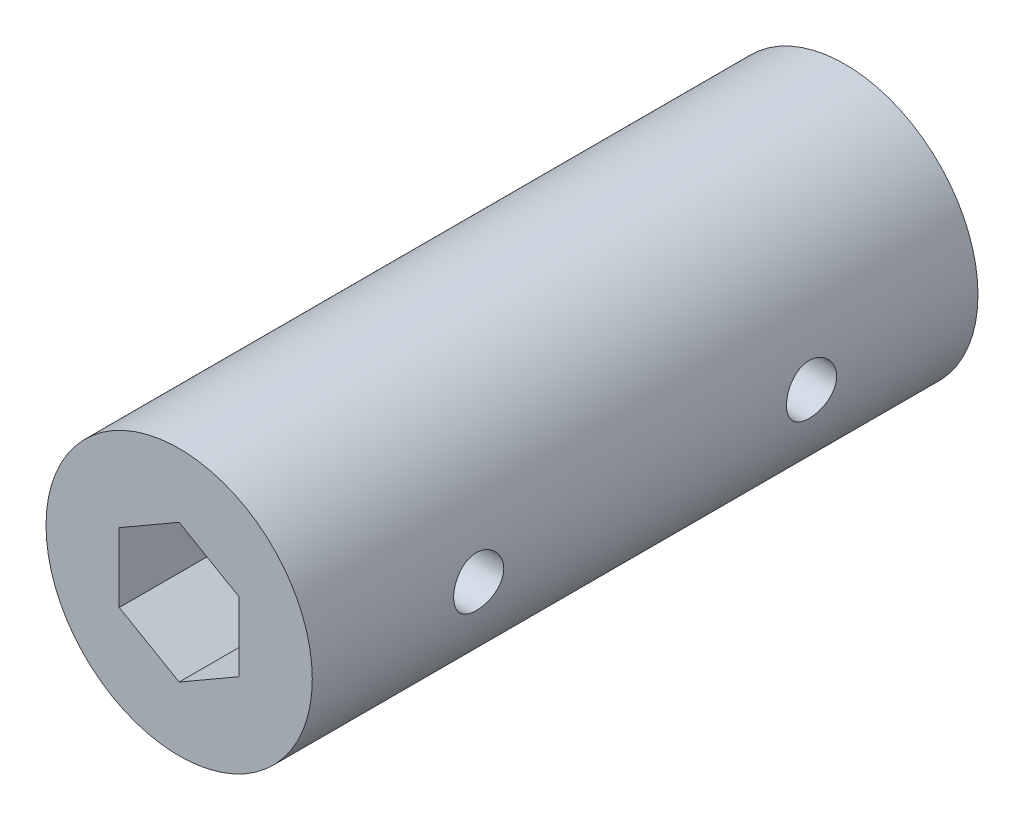
SolidWorks part; units mm, degrees
other "Adapter"
material "Nylon 101"
ref_plane "Front" through (0, 0, 0) normal (0, 0, 1) x (1, 0, 0)
ref_plane "Top" through (0, 0, 0) normal (0, 1, 0) x (1, 0, 0)
ref_plane "Right" through (0, 0, 0) normal (1, 0, 0) x (0, 0, -1)
sketch "MotorSke" plane through (0, 0, 0) normal (0, 0, 1) x (1, 0, 0)
  line L0 (1, 1.05) -> (1, -1.05)
  circle A0 centre (0, 0) radius 2
  arc A1 (1, 1.05) -> (1, -1.05) centre (0, 0) ccw
  dimension "D1" = 1.45
  dimension "D3" = 4
  dimension "D2" = 1
extrude "Motor" add sketch "MotorSke" along normal blind 5
sketch "AxisSke" plane through (0, 0, 5) normal (0, 0, 1) x (1, 0, 0)
  line L0 (1, -1.05) -> (1, 1.05) construction
  line L1 (0, -1.0392) -> (0.9, -0.5196)
  line L2 (0.9, -0.5196) -> (0.9, 0.5196)
  line L3 (0.9, 0.5196) -> (0, 1.0392)
  line L4 (0, 1.0392) -> (-0.9, 0.5196)
  line L5 (-0.9, 0.5196) -> (-0.9, -0.5196)
  line L6 (-0.9, -0.5196) -> (0, -1.0392)
  circle A0 centre (0, 0) radius 0.9 construction
  circle A1 centre (0, 0) radius 2
  dimension "D2" = 4
  dimension "D1" = 1.8
extrude "Axis" add sketch "AxisSke" along normal blind 5
sketch "ScrewHoleSke" plane through (0, 0, 0) normal (1, 0, 0) x (0, 0, -1)
  line L0 (-5, 0) -> (0, 0) construction
  line L1 (-5, 0) -> (-10, 0) construction
  line L2 (-10, 2) -> (-10, -2) construction
  circle A0 centre (-7.5, 0) radius 0.3763
  circle A1 centre (-2.5, 0) radius 0.3763
  point P7 (-7.5, 0)
  point P12 (-2.5, 0)
extrude "ScrewHole" cut sketch "ScrewHoleSke" along normal through all
